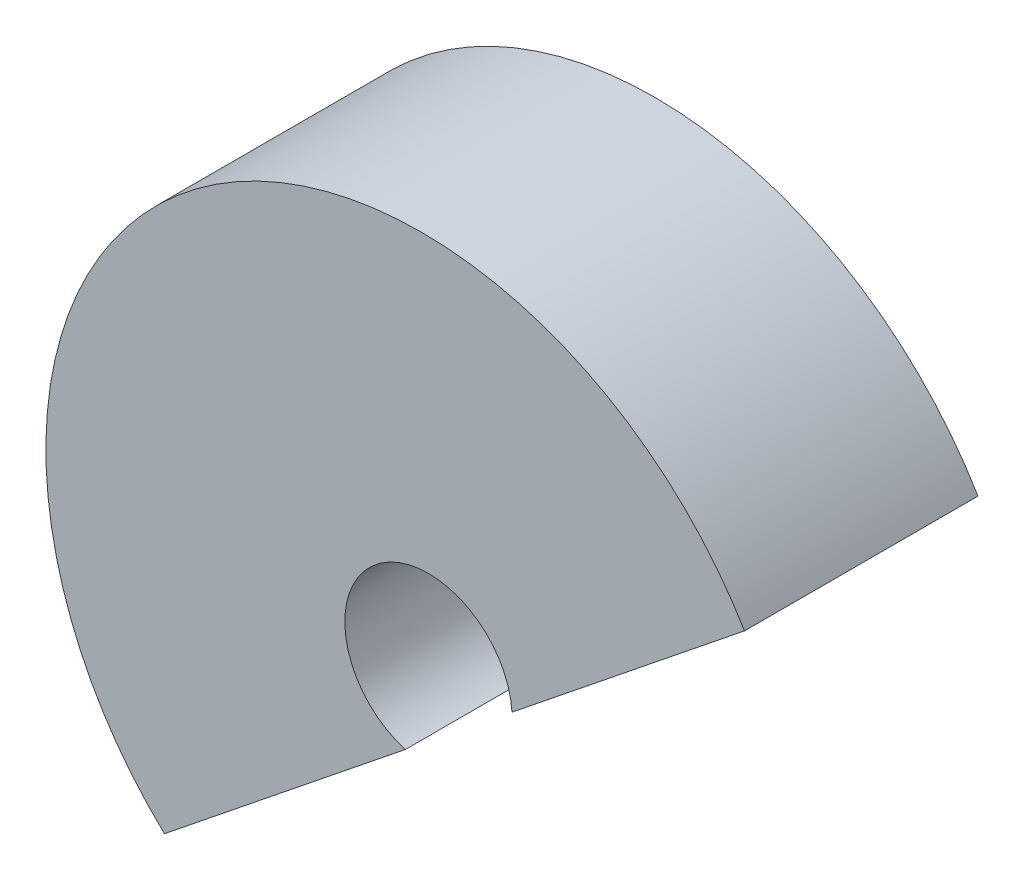
SolidWorks part; units mm, degrees
ref_plane "Front Plane" through (0, 0, 0) normal (0, 0, 1) x (1, 0, 0)
ref_plane "Top Plane" through (0, 0, 0) normal (0, 1, 0) x (1, 0, 0)
ref_plane "Right Plane" through (0, 0, 0) normal (1, 0, 0) x (0, 0, -1)
sketch "Sketch1" plane through (0, 0, 0) normal (0, 0, 1) x (1, 0, 0)
  circle A0 centre (-96.919, 0) radius 64.3454
extrude "Boss-Extrude1" add sketch "Sketch1" along normal blind 40
sketch "Sketch3" plane through (0, 0, 40) normal (0, 0, 1) x (1, 0, 0)
  circle A0 centre (-95.7293, 0) radius 14.3316
  point P7 (-96.919, 64.3454)
extrude "Cut-Extrude2" cut sketch "Sketch3" against normal blind 40
sketch "Sketch4" plane through (0, 0, 40) normal (0, 0, 1) x (1, 0, 0)
  line L0 (-21.117, 49.3027) -> (-148.181, -52.7064)
extrude "Cut-Extrude3" cut sketch "Sketch4" against normal blind 40 and the other way through all
sketch "Sketch5" plane through (-32.3446, 40.2889, 0) normal (0.626, -0.7798, 0) x (0.7798, 0.626, 0)
  circle A0 centre (-34.0927, 19.9001) radius 17.7921
extrude "Cut-Extrude6" cut sketch "Sketch5" against normal blind 18
